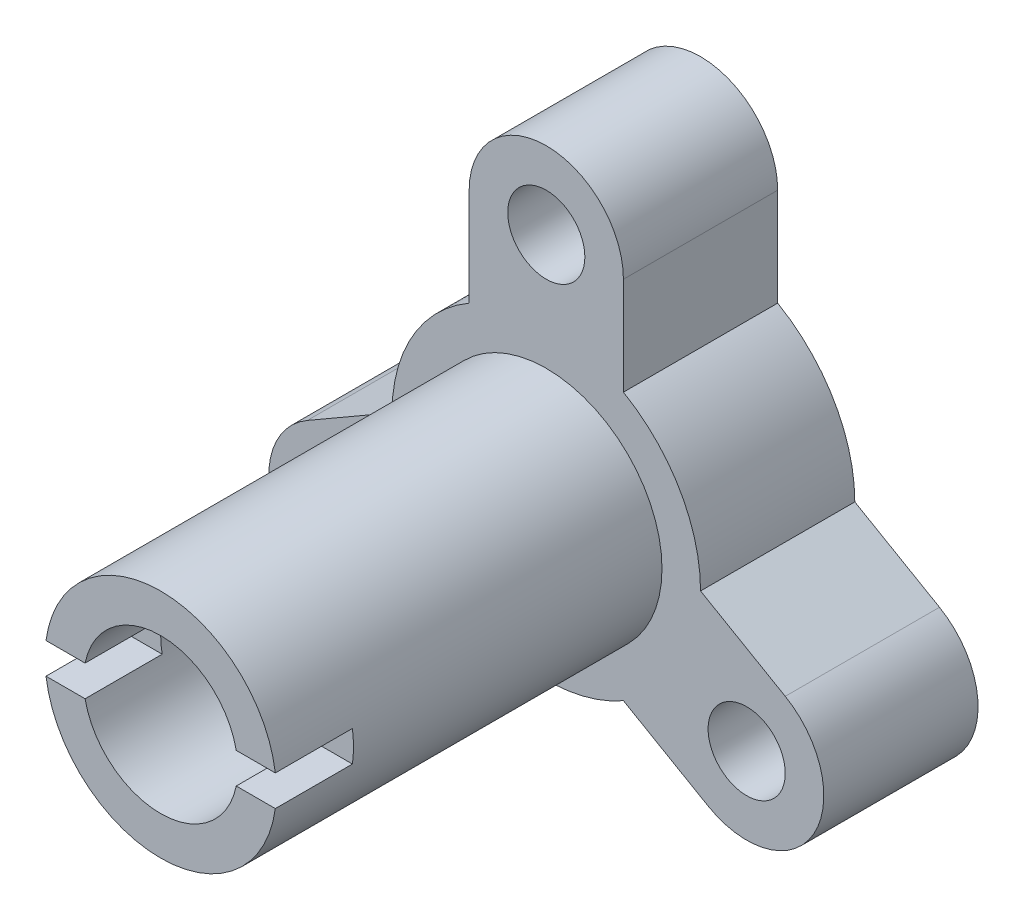
SolidWorks part; units mm, degrees
ref_plane "前基準面" through (0, 0, 0) normal (0, 0, 1) x (1, 0, 0)
ref_plane "上基準面" through (0, 0, 0) normal (0, 1, 0) x (1, 0, 0)
ref_plane "右基準面" through (0, 0, 0) normal (1, 0, 0) x (0, 0, -1)
sketch "草圖1" plane through (0, 0, 0) normal (0, 0, 1) x (1, 0, 0)
  line L0 (0, 37.4217) -> (0, 22.7203) construction
  line L1 (-20.9808, -23.6603) -> (-10, -17.3205)
  line L2 (-10, 30) -> (-10, 17.3205)
  line L3 (-30.9808, -6.3397) -> (-20, 0)
  line L4 (10, 30) -> (10, 17.3205)
  line L5 (30.9808, -6.3397) -> (20, 0)
  line L6 (20.9808, -23.6603) -> (10, -17.3205)
  circle A1 centre (0, 0) radius 20
  circle A2 centre (0, 30) radius 5
  arc A3 (10, 30) -> (-10, 30) centre (0, 30) ccw
  arc A4 (-30.9808, -6.3397) -> (-20.9808, -23.6603) centre (-25.9808, -15) ccw
  circle A5 centre (-25.9808, -15) radius 5
  arc A6 (20.9808, -23.6603) -> (30.9808, -6.3397) centre (25.9808, -15) ccw
  circle A7 centre (25.9808, -15) radius 5
  point P27 (0, 0)
  dimension "D2" = 40
  dimension "D3" = 10
  dimension "D4" = 20
  dimension "D5" = 3
extrude "填料-伸長1" add sketch "草圖1" along normal blind 20
sketch "草圖2" plane through (0, 0, 20) normal (0, 0, 1) x (1, 0, 0)
  circle A0 centre (0, 0) radius 10
  circle A1 centre (0, 0) radius 15
  dimension "D1" = 20
  dimension "D2" = 30
extrude "填料-伸長2" add sketch "草圖2" along normal blind 50
sketch "草圖3" plane through (0, 0, 70) normal (0, 0, 1) x (1, 0, 0)
  line L1 (-26.7916, 2) -> (26.7916, 2)
  line L2 (-26.7916, 2) -> (-26.7916, -2)
  line L3 (-26.7916, -2) -> (26.7916, -2)
  line L4 (26.7916, 2) -> (26.7916, -2)
  line L5 (-26.7916, 2) -> (26.7916, -2) construction
  line L6 (-26.7916, -2) -> (26.7916, 2) construction
  point P0 (0, 0)
  dimension "D1" = 4
extrude "除料-伸長1" cut sketch "草圖3" against normal blind 10
